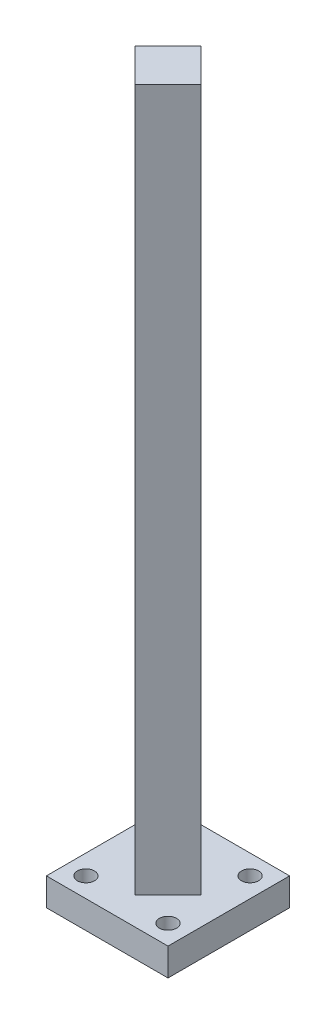
SolidWorks part; units mm, degrees
ref_plane "前视基准面" through (0, 0, 0) normal (0, 0, 1) x (1, 0, 0)
ref_plane "上视基准面" through (0, 0, 0) normal (0, 1, 0) x (1, 0, 0)
ref_plane "右视基准面" through (0, 0, 0) normal (1, 0, 0) x (0, 0, -1)
sketch "草图1" plane through (0, 0, 0) normal (0, 1, 0) x (1, 0, 0)
  line L1 (-11, 11) -> (11, 11)
  line L2 (-11, 11) -> (-11, -11)
  line L3 (-11, -11) -> (11, -11)
  line L4 (11, 11) -> (11, -11)
  line L5 (-11, 11) -> (11, -11) construction
  line L6 (-11, -11) -> (11, 11) construction
  circle A0 centre (-7.4246, 7.4246) radius 1.55
  circle A1 centre (7.4246, 7.4246) radius 1.55
  circle A2 centre (7.4246, -7.4246) radius 1.55
  circle A3 centre (-7.4246, -7.4246) radius 1.55
  point P0 (0, 0)
  point P6 (-7.4246, 7.4246)
  point P18 (0, 0)
  dimension "D4" = 3.1
  dimension "D1" = 22
  dimension "D2" = 22
  dimension "D3" = 10.5
  dimension "D5" = 4
extrude "凸台-拉伸1" add sketch "草图1" along normal blind 5
ref_plane "基准面2" through (0, 5, 0) normal (0, 1, 0) x (1, 0, 0)
sketch "草图2" plane through (0, 5, 0) normal (0, 1, 0) x (1, 0, 0)
  line L0 (0, 0) -> (35355.3391, -35355.3391) construction
  line L1 (0, 0) -> (-35355.3391, -35355.3391) construction
  line L2 (0, 6) -> (-6, 0)
  line L3 (-6, 0) -> (0, -6)
  line L4 (0, -6) -> (6, 0)
  line L5 (6, 0) -> (0, 6)
  point P7 (0, 6)
  point P11 (6, 0)
  point P12 (0, -6)
  point P13 (-6, 0)
  point P14 (0, 0)
  dimension "D2" = 6
  dimension "D1" = 4
extrude "凸台-拉伸2" add sketch "草图2" along normal blind 127
